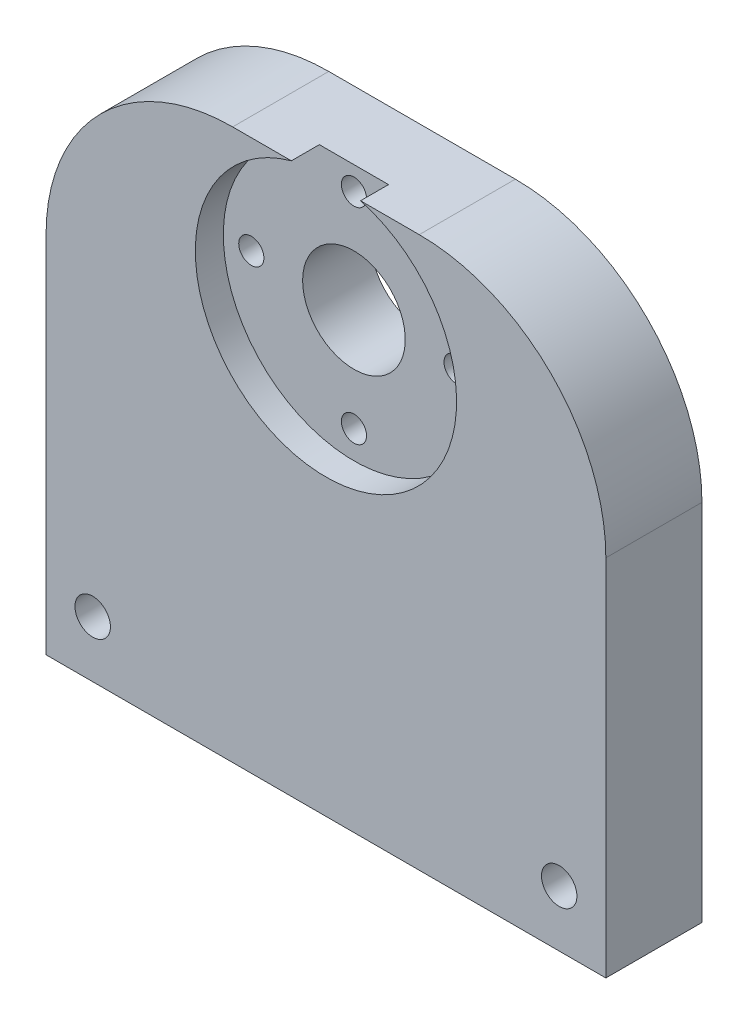
SolidWorks part; units mm, degrees
ref_plane "Ön Düzlem" through (0, 0, 0) normal (0, 0, 1) x (1, 0, 0)
ref_plane "Üst Düzlem" through (0, 0, 0) normal (0, 1, 0) x (1, 0, 0)
ref_plane "Sağ Düzlem" through (0, 0, 0) normal (1, 0, 0) x (0, 0, -1)
sketch "Çizim1" plane through (0, 0, 0) normal (0, 0, 1) x (1, 0, 0)
  line L0 (0, 54.3073) -> (0, -50.6695) construction
  line L1 (-68.447, 0) -> (66.1519, 0) construction
  line L2 (-15.9273, -20.4371) -> (44.0727, -20.4371)
  line L3 (44.0727, -20.4371) -> (44.0727, 18.5629)
  line L4 (24.0727, 38.5629) -> (4.0727, 38.5629)
  line L5 (-15.9273, 18.5629) -> (-15.9273, -20.4371)
  line L6 (-15.9273, -20.4371) -> (-10.9273, -20.4371) construction
  line L7 (-10.9273, -20.4371) -> (-10.9273, -14.3971) construction
  line L8 (44.0727, -20.4371) -> (39.0727, -20.4371) construction
  line L9 (39.0727, -20.4371) -> (39.0727, -14.3971) construction
  line L11 (14.0727, 25.0629) -> (3.0727, 25.0629) construction
  line L12 (3.0727, 25.0629) -> (25.0727, 25.0629) construction
  line L13 (14.0727, 25.0629) -> (14.0727, 36.0629) construction
  line L14 (14.0727, 36.0629) -> (14.0727, 14.0629) construction
  circle A0 centre (-10.9273, -14.3971) radius 1.9
  circle A1 centre (39.0727, -14.3971) radius 1.9
  circle A2 centre (14.0727, 25.0629) radius 5.5
  arc A3 (4.0727, 38.5629) -> (-15.9273, 18.5629) centre (4.0727, 18.5629) ccw
  arc A4 (44.0727, 18.5629) -> (24.0727, 38.5629) centre (24.0727, 18.5629) ccw
  circle A5 centre (3.0727, 25.0629) radius 1.35
  circle A6 centre (14.0727, 36.0629) radius 1.35
  circle A7 centre (25.0727, 25.0629) radius 1.35
  circle A8 centre (14.0727, 14.0629) radius 1.35
  point P22 (-15.9273, 38.5629)
  dimension "D1" = 3.8
  dimension "D2" = 3.8
  dimension "D3" = 59
  dimension "D5" = 20
  dimension "D6" = 20
  dimension "D7" = 6.04
  dimension "D4" = 60
  dimension "D8" = 6.04
  dimension "D9" = 5
  dimension "D10" = 5
extrude "Yükseklik-Ekstrüzyon1" add sketch "Çizim1" along normal blind 10.3
sketch "Çizim2" plane through (0, 0, 10.3) normal (0, 0, 1) x (1, 0, 0)
  circle A0 centre (14.0727, 25.0629) radius 14
extrude "Kes-Ekstrüzyon1" cut sketch "Çizim2" against normal blind 3
